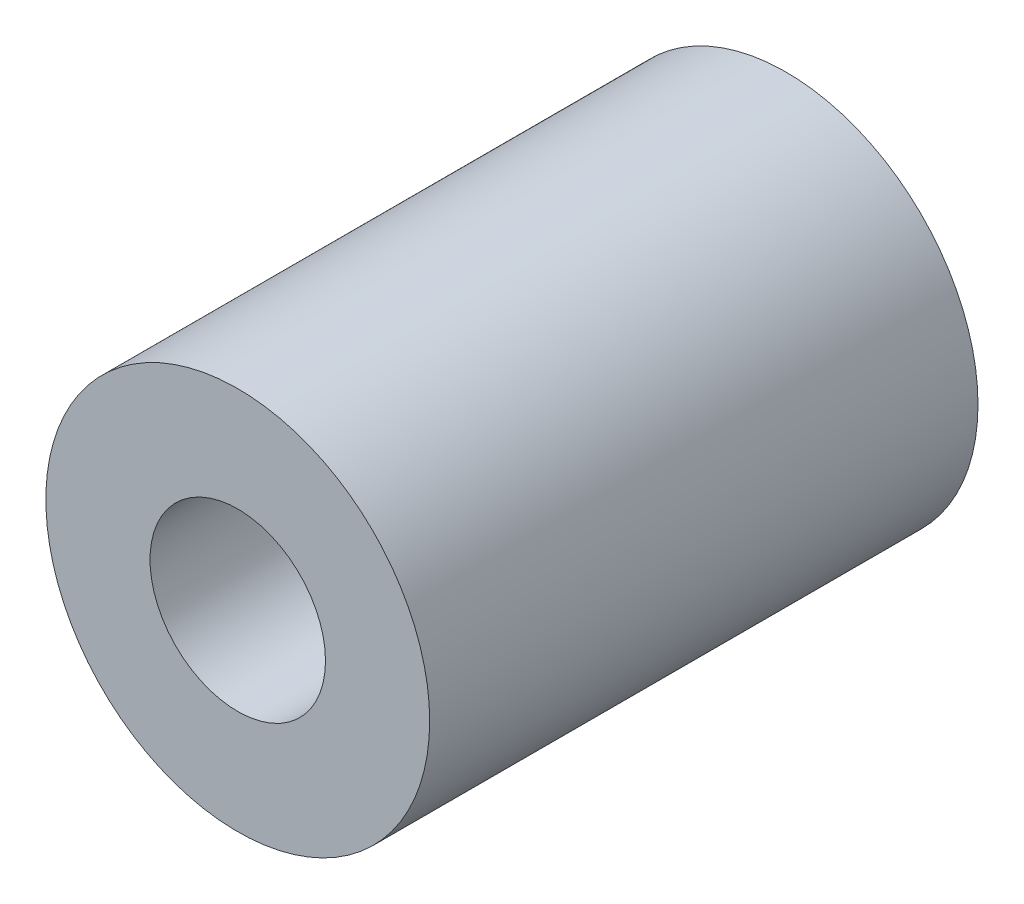
SolidWorks part; units mm, degrees
ref_plane "正面" through (0, 0, 0) normal (0, 0, 1) x (1, 0, 0)
ref_plane "平面" through (0, 0, 0) normal (0, 1, 0) x (1, 0, 0)
ref_plane "右側面" through (0, 0, 0) normal (1, 0, 0) x (0, 0, -1)
sketch "ｽｹｯﾁ1" plane through (0, 0, 0) normal (0, 0, 1) x (1, 0, 0)
  circle A0 centre (0, 0) radius 3.5
  circle A1 centre (0, 0) radius 1.6
  dimension "D1" = 7
  dimension "D2" = 3.2
extrude "ﾎﾞｽ - 押し出し1" add sketch "ｽｹｯﾁ1" along normal blind 10
